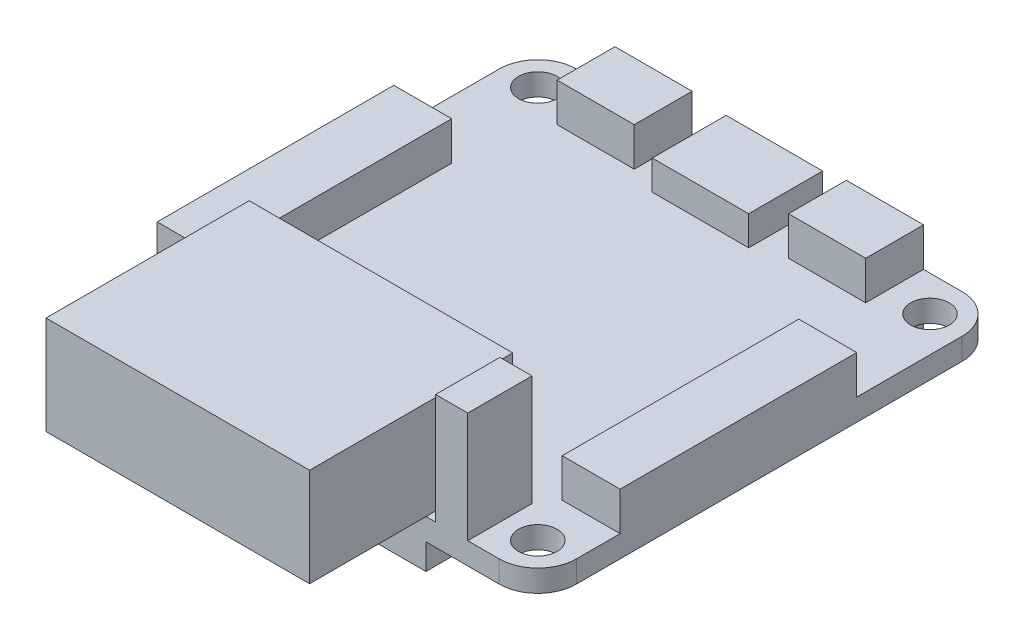
SolidWorks part; units mm, degrees
ref_plane "Front Plane" through (0, 0, 0) normal (0, 0, 1) x (1, 0, 0)
ref_plane "Top Plane" through (0, 0, 0) normal (0, 1, 0) x (1, 0, 0)
ref_plane "Right Plane" through (0, 0, 0) normal (1, 0, 0) x (0, 0, -1)
sketch "Sketch1" plane through (0, 0, 0) normal (0, 1, 0) x (1, 0, 0)
  line L1 (-15, -18) -> (15, -18)
  line L2 (-18, -15) -> (-18, 15)
  line L3 (-15, 18) -> (15, 18)
  line L4 (18, -15) -> (18, 15)
  line L5 (0, 18) -> (0, -18) construction
  line L6 (-18, 0) -> (18, 0) construction
  line L7 (-15.25, -15.25) -> (15.25, -15.25) construction
  line L8 (-15.25, -15.25) -> (-15.25, 15.25) construction
  line L9 (-15.25, 15.25) -> (15.25, 15.25) construction
  line L10 (15.25, -15.25) -> (15.25, 15.25) construction
  line L11 (0, 15.25) -> (0, -15.25) construction
  line L12 (-15.25, 0) -> (15.25, 0) construction
  circle A0 centre (-15.25, 15.25) radius 1.5
  circle A1 centre (15.25, 15.25) radius 1.5
  circle A2 centre (15.25, -15.25) radius 1.5
  circle A3 centre (-15.25, -15.25) radius 1.5
  arc A4 (-15, -18) -> (-18, -15) centre (-15, -15) cw
  arc A5 (15, -18) -> (18, -15) centre (15, -15) ccw
  arc A6 (15, 18) -> (18, 15) centre (15, 15) cw
  arc A7 (-18, 15) -> (-15, 18) centre (-15, 15) cw
  point P0 (0, 0)
  point P4 (0, 0)
  point P14 (-18, -18)
  point P22 (-18, 18)
  dimension "D3" = 3
  dimension "D4" = 3
  dimension "D1" = 36
  dimension "D2" = 30.5
extrude "Boss-Extrude1" add sketch "Sketch1" along normal mid plane 1.7
sketch "Sketch2" plane through (0, 0.85, 0) normal (0, 1, 0) x (1, 0, 0)
  line L0 (-13.3707, -18) -> (-13.3707, -11.6) construction
  line L1 (-15, -18) -> (15, -18) construction
  line L2 (-18, 6.8) -> (-18, -11.6)
  line L3 (-18, 6.8) -> (-13.5, 6.8)
  line L4 (-18, -11.6) -> (-13.5, -11.6)
  line L5 (-13.5, 6.8) -> (-13.5, -11.6)
  line L6 (-18, 15) -> (-18, -15) construction
  line L7 (0, 18) -> (0, -18) construction
  line L8 (15, 18) -> (-15, 18) construction
  line L9 (13.3707, -18) -> (13.3707, -11.6) construction
  line L10 (13.5, 6.8) -> (13.5, -11.6)
  line L11 (18, -11.6) -> (13.5, -11.6)
  line L12 (18, 6.8) -> (13.5, 6.8)
  line L13 (18, 6.8) -> (18, -11.6)
  dimension "D1" = 6.4
  dimension "D2" = 4.5
  dimension "D3" = 18.4
extrude "Boss-Extrude2" add sketch "Sketch2" along normal blind 3
sketch "Sketch3" plane through (0, 0.85, 0) normal (0, 1, 0) x (1, 0, 0)
  line L0 (-18, 15) -> (-12, 15) construction
  line L1 (-12, 18) -> (-6, 18)
  line L2 (-12, 18) -> (-12, 13.5)
  line L3 (-6, 18) -> (-6, 13.5)
  line L4 (-12, 13.5) -> (-6, 13.5)
  line L5 (15, 18) -> (-15, 18) construction
  line L6 (0, 18) -> (0, -18) construction
  line L7 (-15, -18) -> (15, -18) construction
  line L8 (18, 15) -> (12, 15) construction
  line L9 (12, 13.5) -> (6, 13.5)
  line L10 (6, 18) -> (6, 13.5)
  line L11 (12, 18) -> (12, 13.5)
  line L12 (12, 18) -> (6, 18)
  dimension "D1" = 6
  dimension "D2" = 6
  dimension "D3" = 4.5
extrude "Boss-Extrude3" add sketch "Sketch3" along normal blind 3
mirror "Mirror2" about plane through (0, 0, 0) normal (0, 1, 0) of "Boss-Extrude3"
sketch "Sketch4" plane through (0, 0.85, 0) normal (0, 1, 0) x (1, 0, 0)
  line L0 (0, 18) -> (0, -18) construction
  line L1 (6, 18) -> (-6, 18) construction
  line L2 (-15, -18) -> (15, -18) construction
  line L4 (-3.75, 12.65) -> (3.75, 12.65)
  line L5 (-3.75, 12.65) -> (-3.75, 18.4)
  line L6 (-3.75, 18.4) -> (3.75, 18.4)
  line L7 (3.75, 12.65) -> (3.75, 18.4)
  line L8 (0, 18.4) -> (0, 12.65) construction
  line L9 (-3.75, 15.525) -> (3.75, 15.525) construction
  point P6 (0, 15.525)
  dimension "D1" = 7.5
  dimension "D2" = 5.75
  dimension "D3" = 0.4
extrude "Boss-Extrude4" add sketch "Sketch4" along normal blind 2.3
sketch "Sketch5" plane through (0, 0.85, 0) normal (0, 1, 0) x (1, 0, 0)
  line L0 (-15, -18) -> (15, -18) construction
  line L2 (-11.2, -11.25) -> (9.3, -11.25)
  line L3 (-11.2, -11.25) -> (-11.2, -27.05)
  line L4 (-11.2, -27.05) -> (9.3, -27.05)
  line L5 (9.3, -11.25) -> (9.3, -27.05)
  line L6 (-0.95, -27.05) -> (-0.95, -11.25) construction
  line L7 (-11.2, -19.15) -> (9.3, -19.15) construction
  line L8 (18, -15) -> (18, -11.6) construction
  point P0 (0, -18)
  point P1 (0, -18)
  point P7 (18, -13.3)
  point P8 (0, 0)
  point P9 (0, 0)
  dimension "D1" = 20.5
  dimension "D2" = 15.8
  dimension "D3" = 8.7
  dimension "D4" = 6.75
extrude "Boss-Extrude5" add sketch "Sketch5" along normal blind 7.65
sketch "Sketch6" plane through (0, 0.85, 0) normal (0, 1, 0) x (1, 0, 0)
  line L0 (18, -14.2463) -> (11.3, -14.2463) construction
  line L1 (18, -15) -> (18, -11.6) construction
  line L2 (12.55, -18) -> (10.05, -18)
  line L3 (12.55, -18) -> (12.55, -13)
  line L4 (10.05, -18) -> (10.05, -13)
  line L5 (12.55, -13) -> (10.05, -13)
  line L6 (9.3, -18) -> (15, -18) construction
  line L7 (11.3, -13) -> (11.3, -18) construction
  point P12 (0, 0)
  dimension "D1" = 6.7
  dimension "D2" = 5
  dimension "D3" = 2.5
extrude "Boss-Extrude6" add sketch "Sketch6" along normal blind 8.6
sketch "Sketch7" plane through (0, -0.85, 0) normal (0, -1, 0) x (1, 0, 0)
  line L0 (-11.2, 18) -> (9.3, 18)
  line L1 (-11.2, 18) -> (-11.2, 11)
  line L2 (9.3, 18) -> (9.3, 11)
  line L3 (-11.2, 11) -> (9.3, 11)
  dimension "D1" = 7
extrude "Boss-Extrude7" add sketch "Sketch7" along normal blind 2
